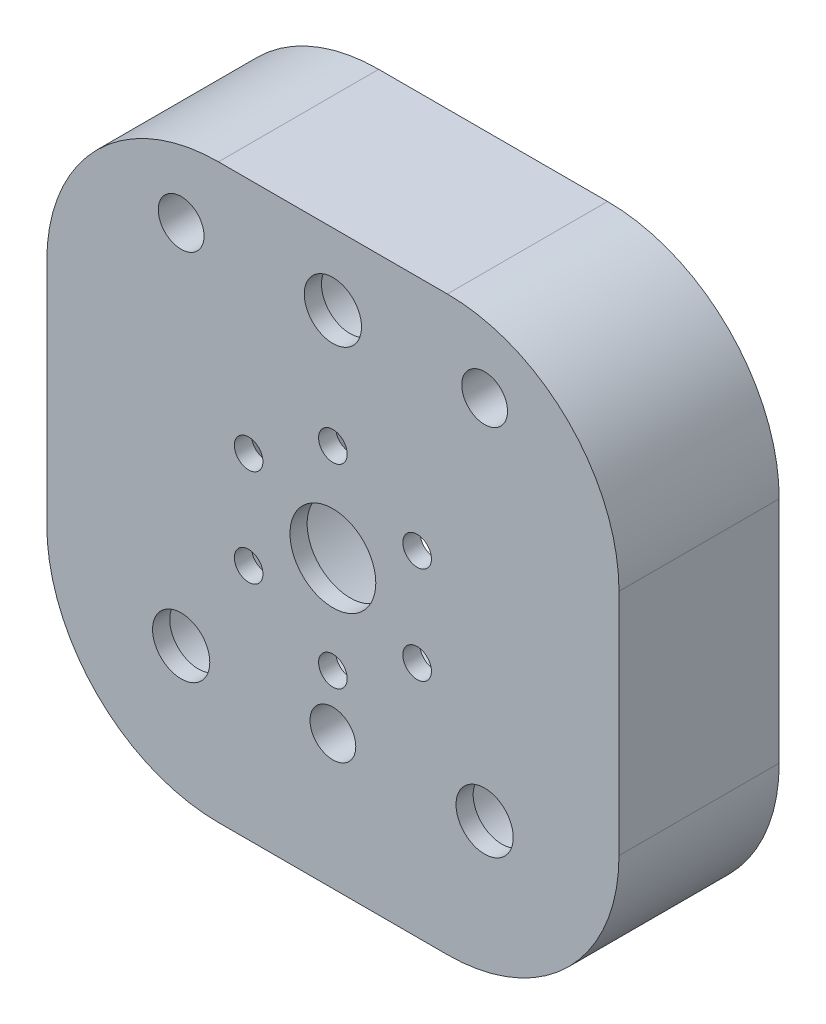
SolidWorks part; units mm, degrees
ref_plane "Front Plane" through (0, 0, 0) normal (0, 0, 1) x (1, 0, 0)
ref_plane "Top Plane" through (0, 0, 0) normal (0, 1, 0) x (1, 0, 0)
ref_plane "Right Plane" through (0, 0, 0) normal (1, 0, 0) x (0, 0, -1)
sketch "Sketch1" plane through (0, 0, 0) normal (0, 0, 1) x (1, 0, 0)
  line L5 (-50, 50) -> (50, 50)
  line L6 (-50, 50) -> (-50, -50)
  line L7 (-50, -50) -> (50, -50)
  line L8 (50, 50) -> (50, -50)
  circle A4 centre (-14.7224, 8.5) radius 2.5 construction
  circle A5 centre (-14.7224, -8.5) radius 2.5 construction
  circle A6 centre (0, -17) radius 2.5 construction
  circle A7 centre (14.7224, -8.5) radius 2.5 construction
  circle A8 centre (14.7224, 8.5) radius 2.5 construction
  circle A9 centre (0, 17) radius 2.5 construction
  circle A10 centre (-14.7224, 8.5) radius 2.5
  circle A11 centre (-14.7224, -8.5) radius 2.5
  circle A12 centre (0, -17) radius 2.5
  circle A13 centre (14.7224, -8.5) radius 2.5
  circle A14 centre (14.7224, 8.5) radius 2.5
  circle A15 centre (0, 17) radius 2.5
  circle A16 centre (0, 0) radius 7.5
  circle A17 centre (0, 37.5) radius 5
  circle A18 centre (-26.5165, -26.5165) radius 5
  circle A19 centre (26.5165, -26.5165) radius 5
  point P5 (0, 50)
  point P17 (-50, 0)
  dimension "D3" = 10
  dimension "D5" = 15
  dimension "D1" = 100
  dimension "D2" = 100
extrude "Boss-Extrude1" add sketch "Sketch1" along normal blind 3
sketch "Sketch2" plane through (0, 0, 0) normal (0, 0, -1) x (-1, 0, 0)
  circle A0 centre (0, 37.5) radius 8.1
  circle A1 centre (26.5165, -26.5165) radius 8.1
  circle A2 centre (-26.5165, -26.5165) radius 8.1
  circle A3 centre (0, 0) radius 22
  dimension "D1" = 16.2
  dimension "D2" = 44
extrude "Boss-Extrude2" add sketch "Sketch2" along normal up to surface (25 mm away)
fillet "Fillet2" radius 3 3 edges at (-26.5165, -34.6165, -25) (0, 29.4, -25) (26.5165, -34.6165, -25)
fillet "Fillet3" radius 3 1 edges at (0, -22, -25)
sketch "Sketch3" plane through (0, 0, 3) normal (0, 0, 1) x (1, 0, 0)
  circle A0 centre (26.5165, 37.5) radius 4
  circle A1 centre (-26.5165, 37.5) radius 4
  circle A2 centre (0, -26.5165) radius 4
  dimension "D1" = 8
extrude "Cut-Extrude1" cut sketch "Sketch3" against normal offset from surface (25 mm away) 3 up to face at (0, -25, -25)
fillet "Fillet4" radius 30 4 edges at (50, -50, -11) (-50, -50, -11) (-50, 50, -11) (50, 50, -11)
